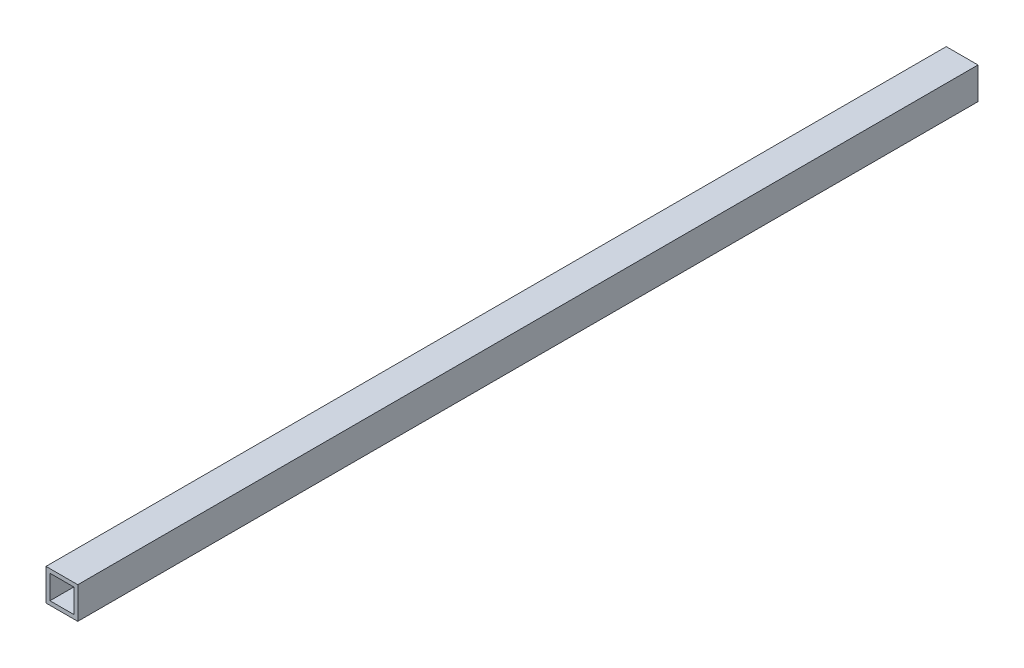
SolidWorks part; units mm, degrees
material "6061-T6 (SS)"
ref_plane "Alzado" through (0, 0, 0) normal (0, 0, 1) x (1, 0, 0)
ref_plane "Planta" through (0, 0, 0) normal (0, 1, 0) x (1, 0, 0)
ref_plane "Vista lateral" through (0, 0, 0) normal (1, 0, 0) x (0, 0, -1)
sketch "Sketch1" plane through (0, 0, 0) normal (0, 0, 1) x (1, 0, 0)
  line L1 (-6, 6) -> (6, 6)
  line L2 (-6, 6) -> (-6, -6)
  line L3 (-6, -6) -> (6, -6)
  line L4 (6, 6) -> (6, -6)
  line L5 (-6, 6) -> (6, -6) construction
  line L6 (-6, -6) -> (6, 6) construction
  point P0 (0, 0)
  dimension "D1" = 12
  dimension "D2" = 12
extrude "Boss-Extrude1" add sketch "Sketch1" along normal blind 340
shell "Shell1" thickness 1.5
equation "\"1.5.00mm\"=2"
